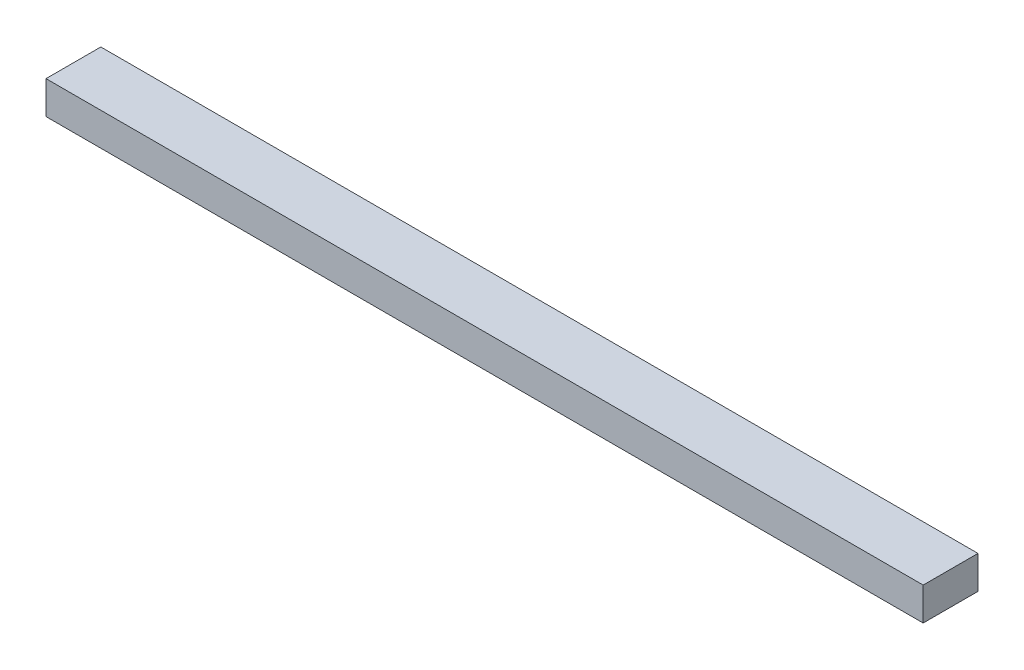
SolidWorks part; units mm, degrees
ref_plane "Front Plane" through (0, 0, 0) normal (0, 0, 1) x (1, 0, 0)
ref_plane "Top Plane" through (0, 0, 0) normal (0, 1, 0) x (1, 0, 0)
ref_plane "Right Plane" through (0, 0, 0) normal (1, 0, 0) x (0, 0, -1)
sketch "Sketch2" plane through (0, 0, 0) normal (0, 1, 0) x (1, 0, 0)
  line L11 (-80, 5) -> (80, 5)
  line L12 (-80, 5) -> (-80, -5)
  line L13 (-80, -5) -> (80, -5)
  line L14 (80, 5) -> (80, -5)
  dimension "D2" = 80
  dimension "D1" = 160
  dimension "D3" = 10
  dimension "D4" = 5
extrude "Boss-Extrude1" add sketch "Sketch2" along normal blind 6
